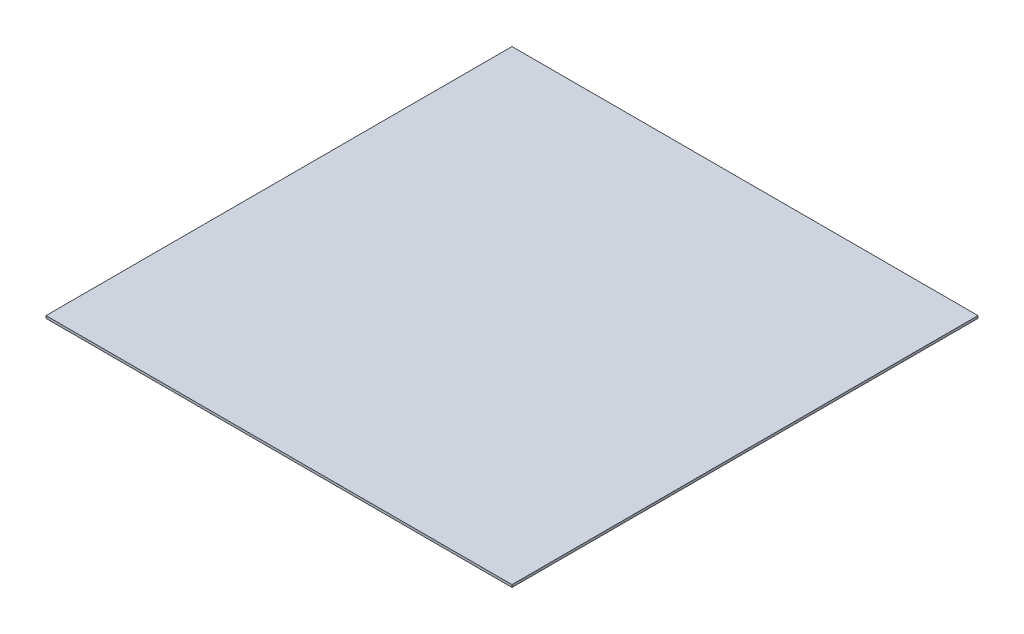
SolidWorks part; units mm, degrees
material "CA"
ref_plane "Front Plane" through (0, 0, 0) normal (0, 0, 1) x (1, 0, 0)
ref_plane "Top Plane" through (0, 0, 0) normal (0, 1, 0) x (1, 0, 0)
ref_plane "Right Plane" through (0, 0, 0) normal (1, 0, 0) x (0, 0, -1)
sketch "Sketch1" plane through (0, 0, 0) normal (0, 1, 0) x (1, 0, 0)
  line L1 (0, 0) -> (566, 0)
  line L2 (0, 0) -> (0, 566)
  line L3 (0, 566) -> (566, 566)
  line L4 (566, 0) -> (566, 566)
  dimension "D1" = 566
  dimension "D2" = 566
extrude "Boss-Extrude1" add sketch "Sketch1" along normal blind 3
